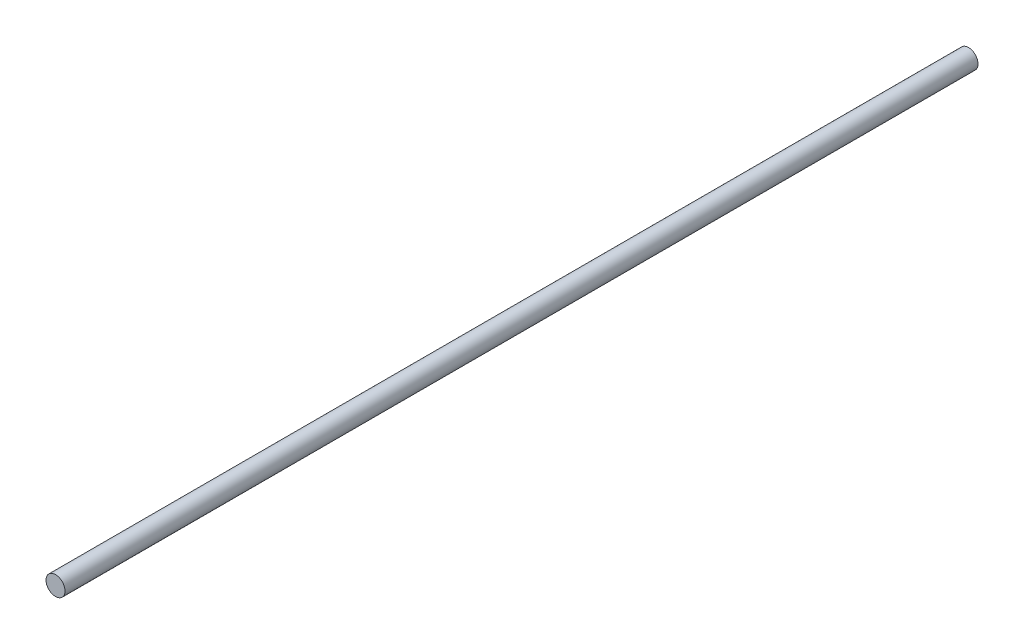
SolidWorks part; units mm, degrees
ref_plane "Front Plane" through (0, 0, 0) normal (0, 0, 1) x (1, 0, 0)
ref_plane "Top Plane" through (0, 0, 0) normal (0, 1, 0) x (1, 0, 0)
ref_plane "Right Plane" through (0, 0, 0) normal (1, 0, 0) x (0, 0, -1)
sketch "Sketch1" plane through (0, 0, 0) normal (0, 0, 1) x (1, 0, 0)
  circle A0 centre (0, 0) radius 0.7937
  dimension "D1" = 1.5875
extrude "Boss-Extrude1" add sketch "Sketch1" along normal blind 76.2
